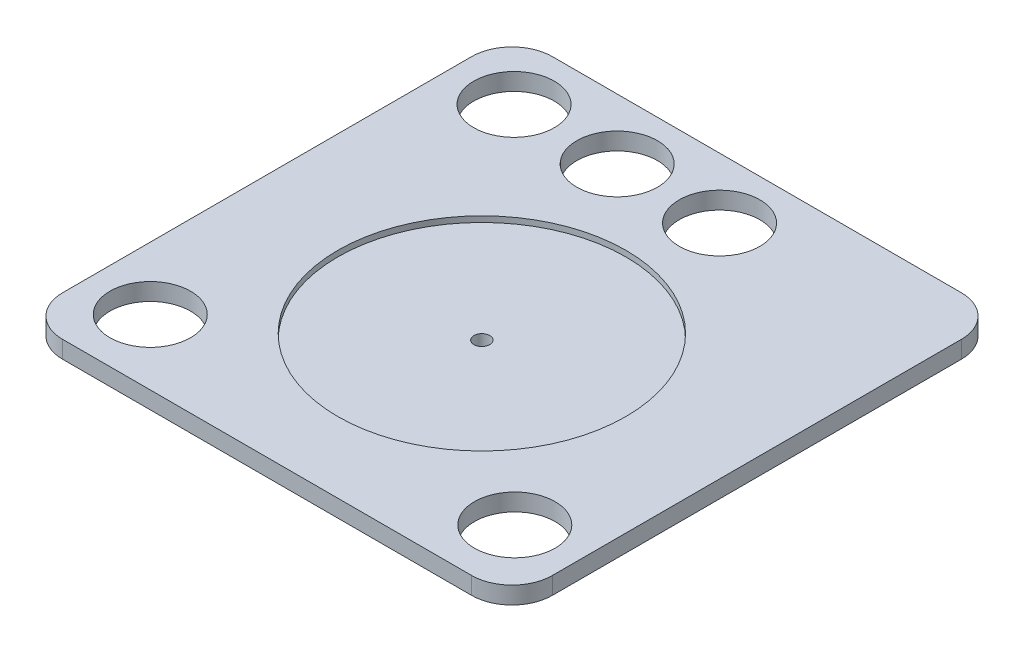
SolidWorks part; units mm, degrees
ref_plane "Front Plane" through (0, 0, 0) normal (0, 0, 1) x (1, 0, 0)
ref_plane "Top Plane" through (0, 0, 0) normal (0, 1, 0) x (1, 0, 0)
ref_plane "Right Plane" through (0, 0, 0) normal (1, 0, 0) x (0, 0, -1)
sketch "Sketch1" plane through (0, 0, 0) normal (0, 1, 0) x (1, 0, 0)
  line L0 (-32.8469, -22.4615) -> (38.1531, -22.4615)
  line L1 (45.1531, -15.4615) -> (45.1531, 55.5385)
  line L2 (38.1531, 62.5385) -> (-32.8469, 62.5385)
  line L3 (-39.8469, 55.5385) -> (-39.8469, -15.4615)
  circle A0 centre (2.6531, 14.807) radius 25
  circle A2 centre (-28.9773, 52.0242) radius 7
  circle A3 centre (-11.0833, 52.0242) radius 7
  circle A4 centre (6.6925, 52.0242) radius 7
  circle A5 centre (-28.9773, -11.118) radius 7
  circle A6 centre (34.2916, -11.118) radius 7
  arc A7 (-32.8469, 62.5385) -> (-39.8469, 55.5385) centre (-32.8469, 55.5385) ccw
  arc A8 (45.1531, 55.5385) -> (38.1531, 62.5385) centre (38.1531, 55.5385) ccw
  arc A9 (38.1531, -22.4615) -> (45.1531, -15.4615) centre (38.1531, -15.4615) ccw
  arc A10 (-39.8469, -15.4615) -> (-32.8469, -22.4615) centre (-32.8469, -15.4615) ccw
  dimension "D1" = 7
  dimension "D2" = 7
  dimension "D3" = 7
  dimension "D4" = 7
extrude "Boss-Extrude1" add sketch "Sketch1" against normal blind 3
sketch "Sketch3" plane through (0, -3, 0) normal (0, -1, 0) x (-1, 0, 0)
  circle A0 centre (-2.6531, 14.807) radius 25
extrude "Boss-Extrude3" add sketch "Sketch3" against normal blind 2
sketch "Sketch4" plane through (0, -1, 0) normal (0, 1, 0) x (1, 0, 0)
  circle A0 centre (2.6531, 14.807) radius 1.375
extrude "Cut-Extrude1" cut sketch "Sketch4" against normal blind 2
